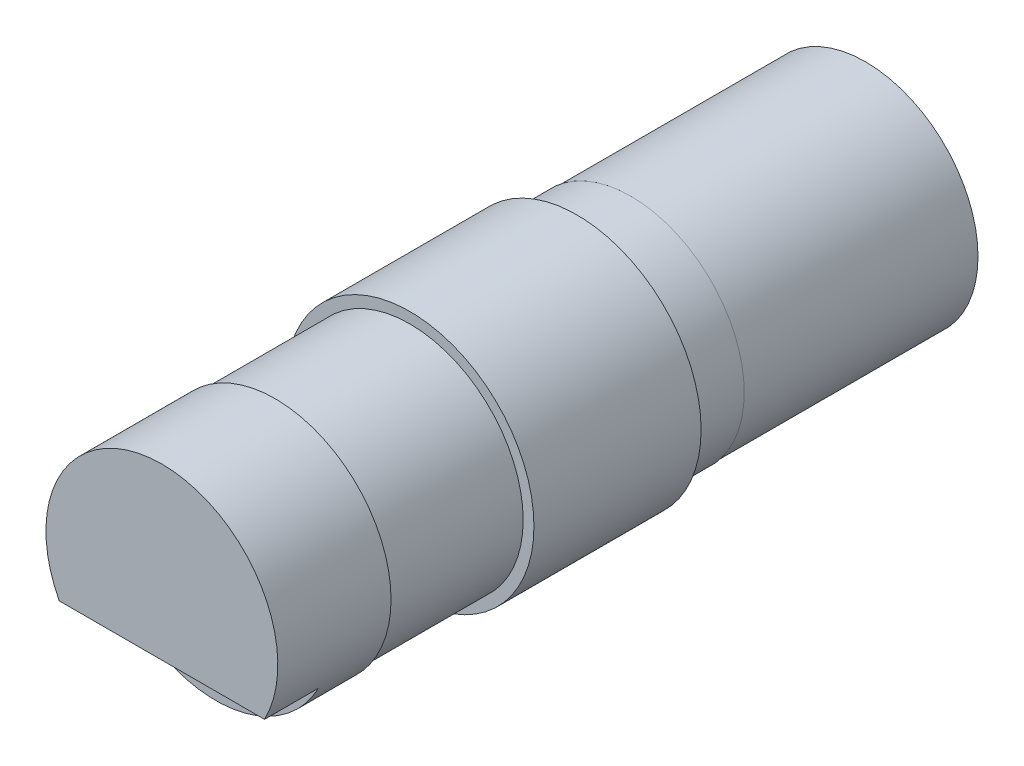
SolidWorks part; units mm, degrees
ref_plane "Front Plane" through (0, 0, 0) normal (0, 0, 1) x (1, 0, 0)
ref_plane "Top Plane" through (0, 0, 0) normal (0, 1, 0) x (1, 0, 0)
ref_plane "Right Plane" through (0, 0, 0) normal (1, 0, 0) x (0, 0, -1)
sketch "Sketch1" plane through (0, 0, 0) normal (0, 0, 1) x (1, 0, 0)
  circle A0 centre (0, 0) radius 21
  dimension "D1" = 42
extrude "Boss-Extrude1" add sketch "Sketch1" against normal blind 25
sketch "Sketch2" plane through (0, 0, -25) normal (0, 0, -1) x (-1, 0, 0)
  circle A0 centre (0, 0) radius 23
  dimension "D1" = 46
extrude "Boss-Extrude2" add sketch "Sketch2" along normal blind 31
sketch "Sketch3" plane through (0, 0, -56) normal (0, 0, -1) x (-1, 0, 0)
  circle A0 centre (0, 0) radius 21
  dimension "D1" = 42
extrude "Boss-Extrude3" add sketch "Sketch3" along normal blind 10
sketch "Sketch4" plane through (0, 0, -66) normal (0, 0, -1) x (-1, 0, 0)
  circle A0 centre (0, 0) radius 20.85
  dimension "D1" = 41.7
extrude "Boss-Extrude4" add sketch "Sketch4" along normal blind 43.5
sketch "Sketch5" plane through (0, 0, -109.5) normal (0, 0, -1) x (-1, 0, 0)
  circle A0 centre (0, 0) radius 13
  dimension "D1" = 26
extrude "Boss-Extrude5" add sketch "Sketch5" along normal blind 2
sketch "Sketch6" plane through (0, 0, -111.5) normal (0, 0, -1) x (-1, 0, 0)
  circle A0 centre (0, 0) radius 4
  dimension "D1" = 8
extrude "Cut-Extrude1" cut sketch "Sketch6" against normal blind 3
sketch "Sketch7" plane through (0, 0, 0) normal (0, 0, 1) x (1, 0, 0)
  circle A0 centre (0, 0) radius 21.5
  dimension "D1" = 43
extrude "Boss-Extrude6" add sketch "Sketch7" along normal blind 21
sketch "Sketch8" plane through (0, 0, 21) normal (0, 0, 1) x (1, 0, 0)
  line L0 (-19.0329, -10) -> (19.0329, -10)
  circle A0 centre (0, 0) radius 21.5 construction
  arc A1 (-19.0329, -10) -> (19.0329, -10) centre (0, 0) ccw
  dimension "D1" = 10
extrude "Cut-Extrude2" cut sketch "Sketch8" against normal blind 10
sketch "Sketch9" plane through (0, 0, -109.5) normal (0, 0, -1) x (-1, 0, 0)
  circle A1 centre (0, 0) radius 17.5 construction
  circle A2 centre (0, 17.5) radius 2
  circle A3 centre (17.5, 0) radius 2
  circle A4 centre (0, -17.5) radius 2
  circle A5 centre (-17.5, 0) radius 2
  point P15 (0, 0)
  dimension "D1" = 35
  dimension "D2" = 4
  dimension "D3" = 4
extrude "Cut-Extrude3" cut sketch "Sketch9" against normal blind 7
